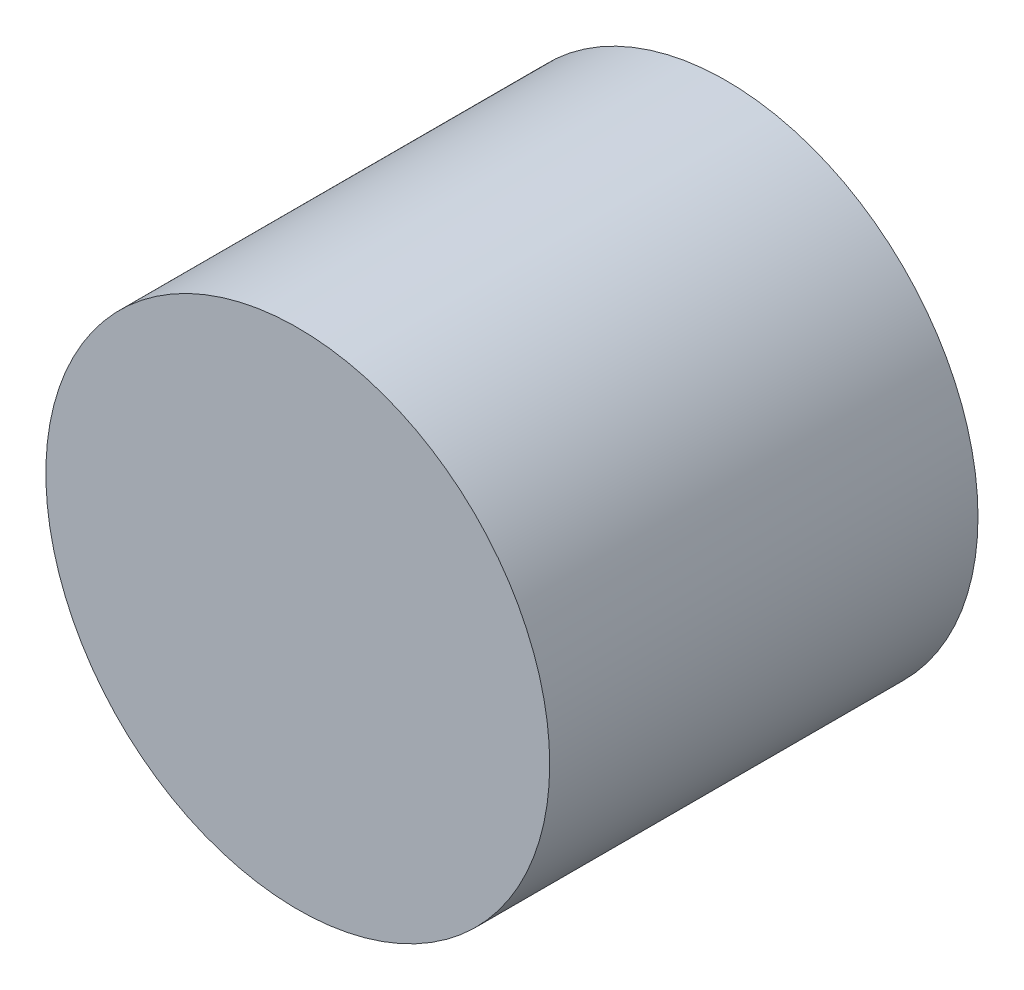
SolidWorks part; units mm, degrees
ref_plane "Front Plane" through (0, 0, 0) normal (0, 0, 1) x (1, 0, 0)
ref_plane "Top Plane" through (0, 0, 0) normal (0, 1, 0) x (1, 0, 0)
ref_plane "Right Plane" through (0, 0, 0) normal (1, 0, 0) x (0, 0, -1)
sketch "Sketch1" plane through (0, 0, 0) normal (0, 0, 1) x (1, 0, 0)
  circle A0 centre (0, 0) radius 10
  dimension "D1" = 20
extrude "Boss-Extrude1" add sketch "Sketch1" along normal blind 17
sketch "Sketch2" plane through (0, 0, 0) normal (0, 0, -1) x (-1, 0, 0)
  circle A0 centre (0, 0) radius 7.5
  circle A1 centre (0, 0) radius 10 construction
  dimension "D1" = 2.5
extrude "Cut-Extrude1" cut sketch "Sketch2" against normal blind 3.5
sketch "Sketch4" plane through (0, 0, 3.5) normal (0, 0, -1) x (-1, 0, 0)
  line L0 (-3.0594, 0.5) -> (3.0594, 0.5)
  line L1 (0, 0) -> (2.6867, 0) construction
  line L2 (-3.0594, -0.5) -> (3.0594, -0.5)
  arc A0 (-3.0594, 0.5) -> (3.0594, 0.5) centre (0, 0) cw
  arc A1 (-3.0594, -0.5) -> (3.0594, -0.5) centre (0, 0) ccw
  dimension "D1" = 3.1
  dimension "D2" = 0.5
extrude "Cut-Extrude2" cut sketch "Sketch4" against normal blind 7
